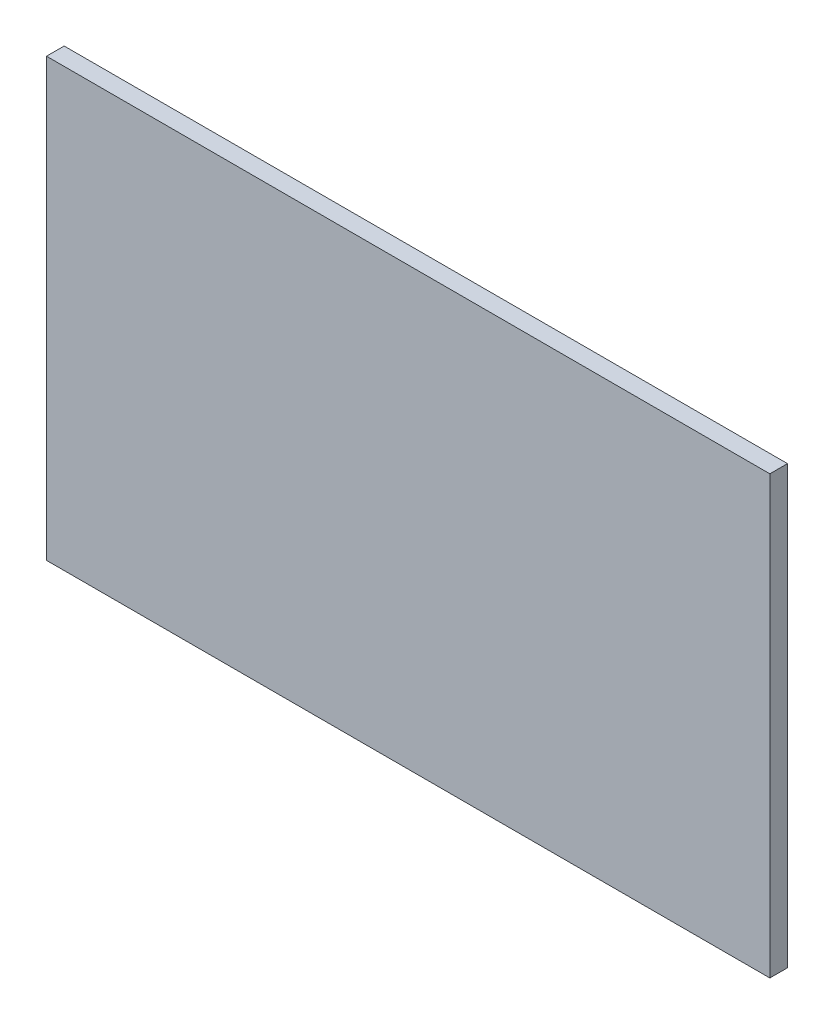
SolidWorks part; units mm, degrees
ref_plane "Plan de face" through (0, 0, 0) normal (0, 0, 1) x (1, 0, 0)
ref_plane "Plan de dessus" through (0, 0, 0) normal (0, 1, 0) x (1, 0, 0)
ref_plane "Plan de droite" through (0, 0, 0) normal (1, 0, 0) x (0, 0, -1)
sketch "Esquisse1" plane through (0, 0, 0) normal (0, 0, 1) x (1, 0, 0)
  line L1 (0, 0) -> (1640, 0)
  line L2 (0, 0) -> (0, 990)
  line L3 (0, 990) -> (1640, 990)
  line L4 (1640, 0) -> (1640, 990)
  dimension "D1" = 1640
  dimension "D2" = 990
extrude "Boss.-Extru.1" add sketch "Esquisse1" along normal blind 40
